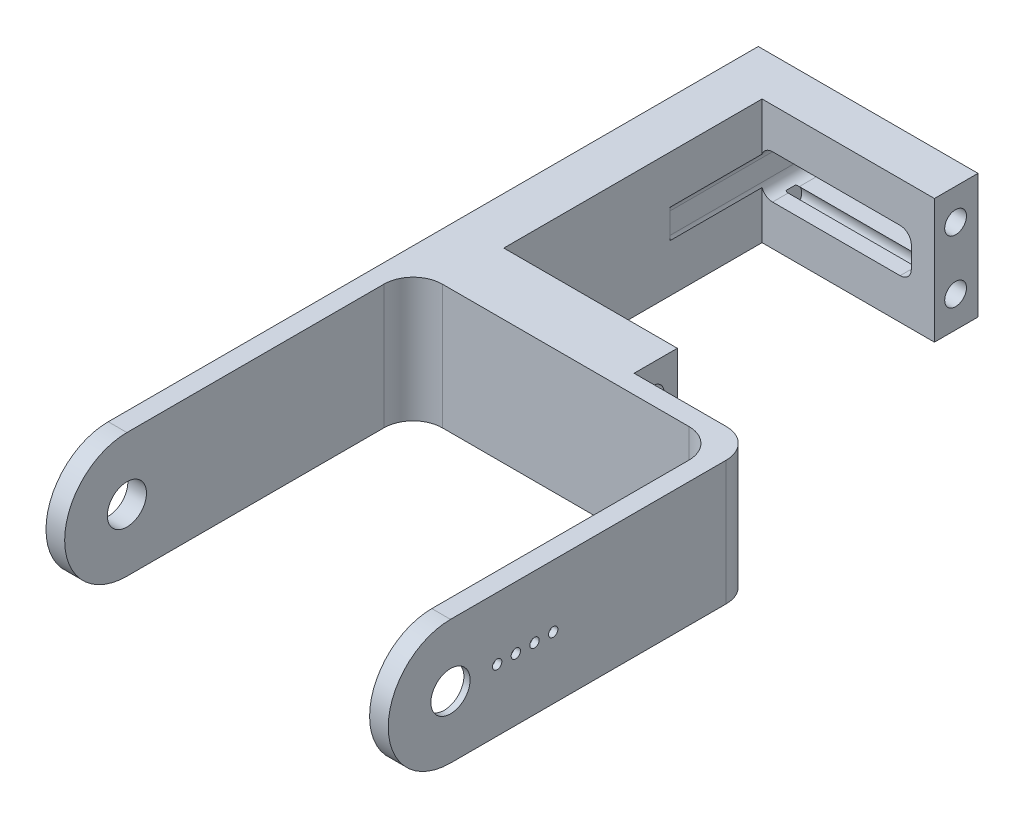
SolidWorks part; units mm, degrees
ref_plane "Vorne" through (0, 0, 0) normal (0, 0, 1) x (1, 0, 0)
ref_plane "Oben" through (0, 0, 0) normal (0, 1, 0) x (1, 0, 0)
ref_plane "Rechts" through (0, 0, 0) normal (1, 0, 0) x (0, 0, -1)
sketch "Skizze1" plane through (0, 0, 0) normal (0, 1, 0) x (1, 0, 0)
  line L1 (0, 0) -> (55, 0)
  line L2 (0, 0) -> (0, 59)
  line L3 (0, 59) -> (50.3, 59)
  line L4 (55, 0) -> (55, 54.3)
  line L5 (52, 0) -> (3, 0)
  line L6 (52, 0) -> (52, 51.3)
  line L7 (47.3, 56) -> (7.7, 56)
  line L8 (3, 0) -> (3, 51.3)
  arc A0 (52, 51.3) -> (47.3, 56) centre (47.3, 51.3) ccw
  arc A1 (7.7, 56) -> (3, 51.3) centre (7.7, 51.3) ccw
  arc A2 (50.3, 59) -> (55, 54.3) centre (50.3, 54.3) cw
  dimension "D6" = 4.7
  dimension "D7" = 4.7
  dimension "D1" = 59
  dimension "D2" = 55
  dimension "D3" = 3
  dimension "D4" = 3
  dimension "D5" = 3
extrude "Aufsatz-Linear austragen1" add sketch "Skizze1" along normal blind 20 contours L1 L8 L7 L6 L4 L3 L2
sketch "Skizze2" plane through (55, 0, 0) normal (1, 0, 0) x (0, 0, -1)
  line L0 (0, 20) -> (0, 0) construction
  line L1 (10, 20) -> (0, 20)
  line L2 (0, 20) -> (0, 0)
  line L3 (0, 0) -> (10, 0)
  arc A0 (10, 20) -> (10, 0) centre (10, 10) ccw
  line M1 (0, 0) -> (54.3, 0)
  line M3 (54.3, 20) -> (0, 20)
  line M4 (0, 20) -> (0, 0)
  dimension "D1" = 10
extrude "Schnitt-Linear austragen1" cut sketch "Skizze2" against normal through all contours A0 M3 M4 | A0 L2 M1
sketch "Skizze3" plane through (55, 0, 0) normal (1, 0, 0) x (0, 0, -1)
  circle A0 centre (10, 10) radius 3.15
  dimension "D1" = 6.3
extrude "Schnitt-Linear austragen2" cut sketch "Skizze3" against normal through all
sketch "Skizze4" plane through (52, 0, 0) normal (-1, 0, 0) x (0, 0, 1)
  line L2 (-27.5, 7.5) -> (-12.8239, 4.1455)
  line L3 (-27.5, 12.5) -> (-12.8239, 15.8545)
  arc A0 (-12.8239, 4.1455) -> (-12.8239, 15.8545) centre (-10, 10) ccw
  arc A1 (-27.5, 12.5) -> (-27.5, 7.5) centre (-27.5, 10) ccw
  arc A2 (-10, 0) -> (-10, 20) centre (-10, 10) ccw construction
  dimension "D1" = 0
extrude "Schnitt-Linear austragen3" cut sketch "Skizze4" against normal blind 2
sketch "Skizze5" plane through (54, 0, 0) normal (-1, 0, 0) x (0, 0, 1)
  circle A0 centre (-26.5, 10) radius 0.75
  circle A1 centre (-23.5, 10) radius 0.75
  circle A2 centre (-20.5, 10) radius 0.75
  circle A3 centre (-17.5, 10) radius 0.75
  circle A4 centre (-10, 10) radius 3.15 construction
  dimension "D1" = 3
  dimension "D2" = 3
  dimension "D3" = 3
  dimension "D4" = 7.5
  dimension "D5" = 0
extrude "Schnitt-Linear austragen4" cut sketch "Skizze5" against normal blind 2
sketch "Skizze6" plane through (0, 0, 0) normal (0, -1, 0) x (1, 0, 0)
  line L0 (0, -59) -> (50.3, -59) construction
  line L3 (35.5, -65.9553) -> (0, -65.9553)
  line L4 (0, -59) -> (0, -65.9553)
  line L7 (0, -59) -> (35.5, -59)
  line L9 (35.5, -65.9553) -> (35.5, -59)
  dimension "D1" = 0
  dimension "D3" = 35.5
extrude "Aufsatz-Linear austragen2" add sketch "Skizze6" against normal blind 20
sketch "Skizze7" plane through (0, 0, 0) normal (0, -1, 0) x (1, 0, 0)
  line L1 (0, -65.9553) -> (7.6117, -65.9553)
  line L2 (0, -65.9553) -> (0, -119.1478)
  line L3 (0, -119.1478) -> (7.6117, -119.1478)
  line L4 (7.6117, -65.9553) -> (7.6117, -119.1478)
extrude "Aufsatz-Linear austragen3" add sketch "Skizze7" against normal blind 20
sketch "Skizze8" plane through (7.6117, 0, 0) normal (1, 0, 0) x (0, 0, -1)
  line L0 (65.9553, 20) -> (65.9553, 0) construction
  line L1 (114.4553, 20) -> (107.4553, 20)
  line L2 (114.4553, 20) -> (114.4553, 0)
  line L3 (114.4553, 0) -> (107.4553, 0)
  line L4 (107.4553, 20) -> (107.4553, 0)
  line L5 (119.1478, 0) -> (65.9553, 0) construction
  point P5 (119.1478, 0)
  dimension "D1" = 0
  dimension "D2" = 41.5
  dimension "D3" = 7
extrude "Aufsatz-Linear austragen4" add sketch "Skizze8" along normal blind 27.7
sketch "Skizze9" plane through (0, 0, -119.1478) normal (0, 0, -1) x (-1, 0, 0)
  line L0 (0, 20) -> (-7.6117, 20) construction
  line L1 (-9.3, 13.5) -> (-29.794, 13.5)
  line L2 (-7.5, 11.7) -> (-7.5, 8.3)
  line L3 (-9.3, 6.5) -> (-29.794, 6.5)
  line L4 (-31.594, 11.7) -> (-31.594, 8.3)
  line L5 (0, 0) -> (-7.6117, 0) construction
  line L7 (0, 20) -> (0, 0) construction
  arc A0 (-9.3, 13.5) -> (-7.5, 11.7) centre (-9.3, 11.7) cw
  arc A1 (-7.5, 8.3) -> (-9.3, 6.5) centre (-9.3, 8.3) cw
  arc A2 (-29.794, 6.5) -> (-31.594, 8.3) centre (-29.794, 8.3) cw
  arc A3 (-29.794, 13.5) -> (-31.594, 11.7) centre (-29.794, 11.7) ccw
  dimension "D5" = 1.8
  dimension "D1" = 6.5
  dimension "D2" = 6.5
  dimension "D4" = 7.5
extrude "Schnitt-Linear austragen5" cut sketch "Skizze9" against normal blind 26.48
sketch "Skizze10" plane through (35.3117, 0, 0) normal (1, 0, 0) x (0, 0, -1)
  line L1 (59, 20) -> (59, 0) construction
  line L2 (114.4553, 20) -> (107.4553, 20) construction
  line L3 (107.4553, 0) -> (114.4553, 0) construction
  line L4 (65.9553, 0) -> (59, 0) construction
  line L5 (65.9553, 20) -> (59, 20) construction
  circle A4 centre (62.0553, 15) radius 1.75
  circle A5 centre (62.0553, 5) radius 1.75
  circle A6 centre (110.8553, 5) radius 1.75
  circle A7 centre (110.8553, 15) radius 1.75
  dimension "D1" = 3.5
  dimension "D2" = 3.5
  dimension "D3" = 3.5
  dimension "D4" = 3.5
  dimension "D5" = 3.0553
  dimension "D6" = 3.0553
  dimension "D7" = 51.8553
  dimension "D8" = 51.8553
  dimension "D9" = 5
  dimension "D10" = 5
  dimension "D11" = 5
  dimension "D12" = 5
extrude "Schnitt-Linear austragen6" cut sketch "Skizze10" against normal blind 26.48 and the other way blind 6
sketch "Skizze11" plane through (0, 0, 0) normal (-1, 0, 0) x (0, 0, 1)
  circle A1 centre (-96.9553, 10) radius 3
  dimension "D1" = 6
extrude "Aufsatz-Linear austragen5" add sketch "Skizze11" along normal blind 4
sketch "Skizze12" plane through (7.6117, 0, 0) normal (1, 0, 0) x (0, 0, -1)
  line L1 (114.4553, 20) -> (119.1478, 20)
  line L2 (114.4553, 20) -> (114.4553, 0)
  line L3 (114.4553, 0) -> (119.1478, 0)
  line L4 (119.1478, 20) -> (119.1478, 0)
extrude "Schnitt-Linear austragen7" cut sketch "Skizze12" against normal through all
